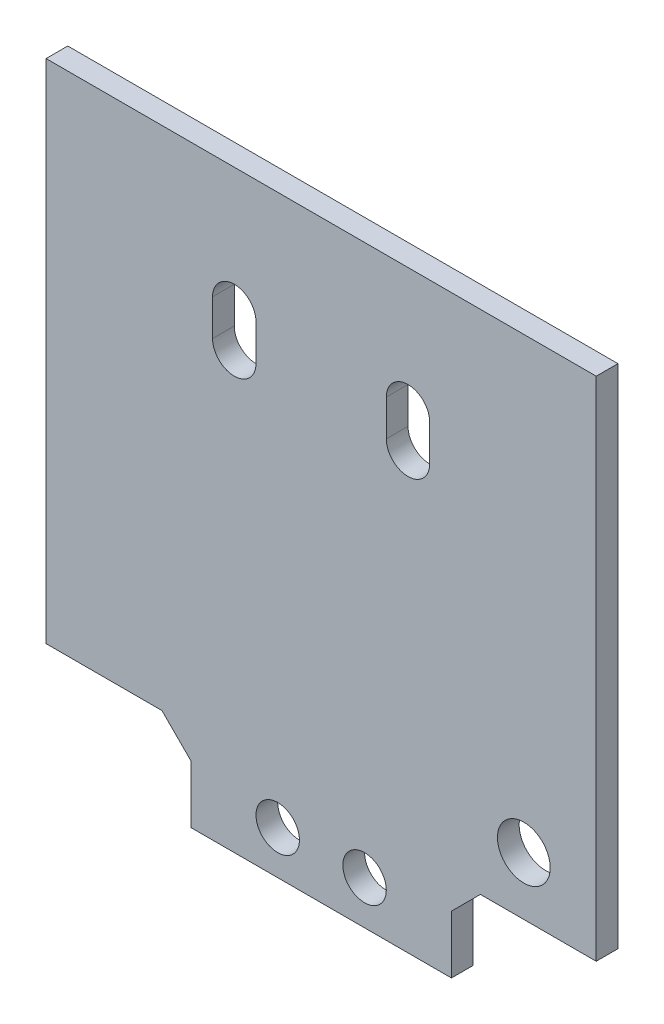
SolidWorks part; units mm, degrees
ref_plane "Płaszczyzna przednia" through (0, 0, 0) normal (0, 0, 1) x (1, 0, 0)
ref_plane "Płaszczyzna górna" through (0, 0, 0) normal (0, 1, 0) x (1, 0, 0)
ref_plane "Płaszczyzna prawa" through (0, 0, 0) normal (1, 0, 0) x (0, 0, -1)
sketch "Szkic1" plane through (0, 0, 0) normal (0, 0, 1) x (1, 0, 0)
  line L0 (0, 0) -> (38, 0)
  line L1 (38, 0) -> (38, -35)
  line L2 (38, -35) -> (31.0601, -35)
  line L4 (28, -40.3971) -> (28, -41)
  line L5 (28, -41) -> (10, -41)
  line L6 (10, -41) -> (10, -40.6999)
  line L8 (5.8893, -35) -> (0, -35)
  line L9 (0, -35) -> (0, 0)
  line L10 (5.8893, -35) -> (10, -35)
  line L11 (10, -35) -> (10, -40.6999)
  line L12 (31.0601, -35) -> (28, -35)
  line L13 (28, -35) -> (28, -40.3971)
  line L14 (8.729, -38) -> (30.3051, -38) construction
  line L15 (25, -8.5) -> (25, -11) construction
  line L16 (26.5, -8.5) -> (26.5, -11)
  line L17 (23.5, -8.5) -> (23.5, -11)
  line L18 (19, 0) -> (19, -41) construction
  line L19 (13, -8.5) -> (13, -11) construction
  line L20 (11.5, -8.5) -> (11.5, -11)
  line L21 (14.5, -8.5) -> (14.5, -11)
  circle A0 centre (16, -38) radius 1.5
  circle A1 centre (22, -38) radius 1.5
  circle A2 centre (33, -31) radius 1.8224
  arc A3 (26.5, -8.5) -> (23.5, -8.5) centre (25, -8.5) ccw
  arc A4 (23.5, -11) -> (26.5, -11) centre (25, -11) ccw
  arc A5 (11.5, -8.5) -> (14.5, -8.5) centre (13, -8.5) cw
  arc A6 (14.5, -11) -> (11.5, -11) centre (13, -11) cw
  point P23 (25, -9.75)
  point P28 (25, -7)
  point P33 (13, -9.75)
  dimension "D10" = 3
  dimension "D11" = 3
  dimension "D14" = 1.5
  dimension "D17" = 11
  dimension "D1" = 38
  dimension "D2" = 35
  dimension "D3" = 35
  dimension "D4" = 6
  dimension "D5" = 10
  dimension "D6" = 10
  dimension "D7" = 3
  dimension "D8" = 16
  dimension "D9" = 16
  dimension "D12" = 5
  dimension "D13" = 4
  dimension "D15" = 13
  dimension "D16" = 7
extrude "Dodanie-wyciągnięcie1" add sketch "Szkic1" along normal blind 1.5
chamfer "Sfazowanie1" distance 2 angle 45 2 edges at (10, -35, 0.75) (28, -35, 0.75)
